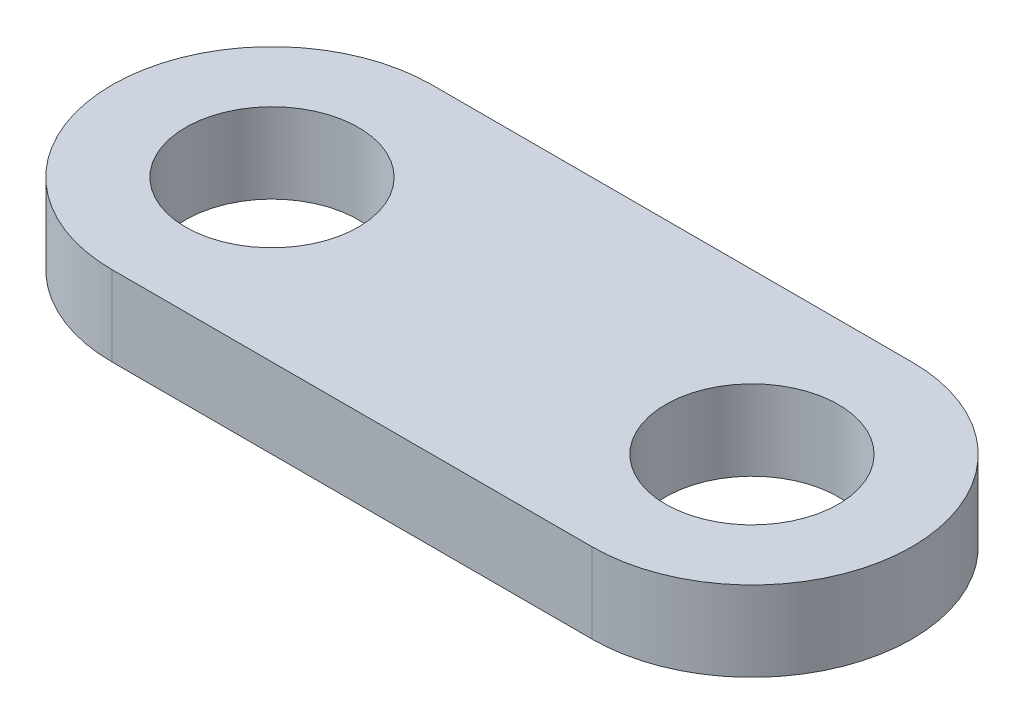
SolidWorks part; units mm, degrees
ref_plane "Front Plane" through (0, 0, 0) normal (0, 0, 1) x (1, 0, 0)
ref_plane "Top Plane" through (0, 0, 0) normal (0, 1, 0) x (1, 0, 0)
ref_plane "Right Plane" through (0, 0, 0) normal (1, 0, 0) x (0, 0, -1)
sketch "Sketch1" plane through (0, 0, 0) normal (0, 1, 0) x (1, 0, 0)
  line L0 (-7.5, 0) -> (7.5, 0) construction
  line L1 (-7.5, 5) -> (7.5, 5)
  line L2 (-7.5, -5) -> (7.5, -5)
  arc A0 (-7.5, 5) -> (-7.5, -5) centre (-7.5, 0) ccw
  arc A1 (7.5, -5) -> (7.5, 5) centre (7.5, 0) ccw
  circle A2 centre (-7.5, 0) radius 2.7
  circle A3 centre (7.5, 0) radius 2.7
  point P2 (0, 0)
  dimension "D2" = 5
  dimension "D3" = 5.4
  dimension "D1" = 15
extrude "Boss-Extrude1" add sketch "Sketch1" along normal blind 2.5
